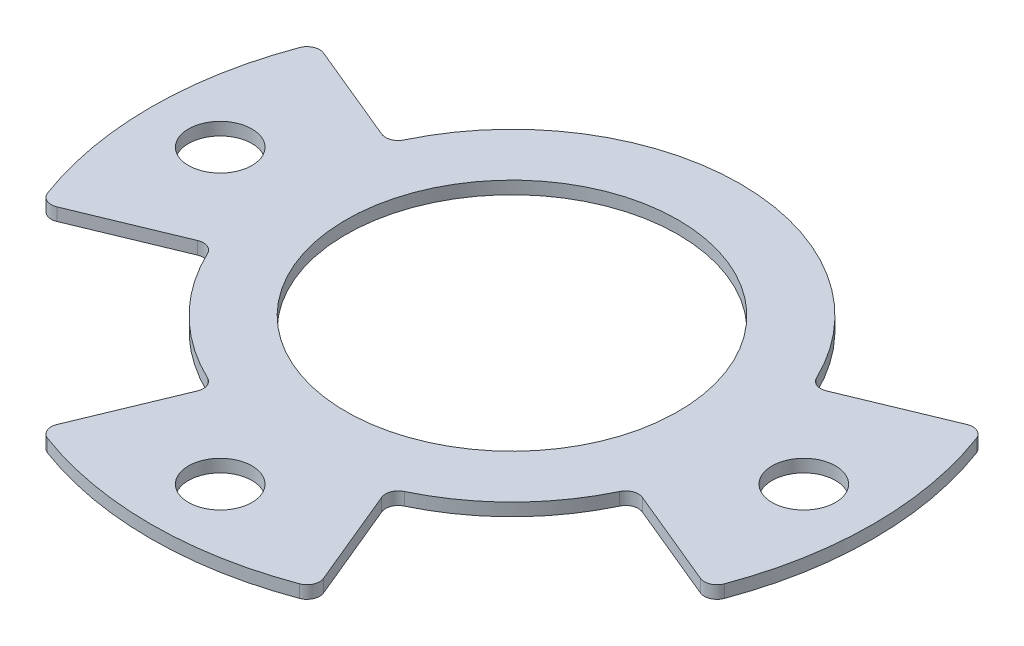
SolidWorks part; units mm, degrees
ref_plane "Front Plane" through (0, 0, 0) normal (0, 0, 1) x (1, 0, 0)
ref_plane "Top Plane" through (0, 0, 0) normal (0, 1, 0) x (1, 0, 0)
ref_plane "Right Plane" through (0, 0, 0) normal (1, 0, 0) x (0, 0, -1)
sketch "Sketch1" plane through (0, 0, 0) normal (0, 1, 0) x (1, 0, 0)
  circle A0 centre (0, 0) radius 72.3
  dimension "D1" = 144.6
extrude "Extrude1" add sketch "Sketch1" along normal blind 2.54
sketch "Sketch2" plane through (0, 0, 0) normal (0, -1, 0) x (1, 0, 0)
  line L0 (0, 0) -> (0, 46.2536) construction
  circle A0 centre (-58.42, 0) radius 6.35
  circle A1 centre (58.42, 0) radius 6.35
  circle A2 centre (0, 58.42) radius 6.35
  dimension "D1" = 12.7
  dimension "D2" = 12.7
  dimension "D3" = 116.84
  dimension "D4" = 58.42
extrude "Extrude2" cut sketch "Sketch2" against normal through all
sketch "Sketch3" plane through (0, 0, 0) normal (0, -1, 0) x (1, 0, 0)
  circle A0 centre (0, 0) radius 33.25
  dimension "D1" = 66.5
extrude "Extrude3" cut sketch "Sketch3" against normal through all
sketch "Sketch4" plane through (0, 0, 0) normal (0, -1, 0) x (1, 0, 0)
  line L0 (-42.2398, -17.4963) -> (-196.0271, -81.1971)
  line L1 (-196.0271, -81.1971) -> (196.0271, -81.1971)
  line L2 (196.0271, -81.1971) -> (42.2398, -17.4963)
  line L4 (0, 0) -> (0, 78.8399) construction
  line L5 (-42.2398, 17.4963) -> (-90.2628, 37.3881)
  line L6 (-90.2628, 37.3881) -> (-35.0925, 84.7207)
  line L7 (-35.0925, 84.7207) -> (-17.4963, 42.2398)
  line L8 (42.2398, 17.4963) -> (90.2628, 37.3881)
  line L9 (35.0925, 84.7207) -> (17.4963, 42.2398)
  line L10 (90.2628, 37.3881) -> (35.0925, 84.7207)
  arc A0 (-17.4963, 42.2398) -> (-42.2398, 17.4963) centre (0, 0) ccw
  arc A1 (17.4963, 42.2398) -> (42.2398, 17.4963) centre (0, 0) cw
  arc A2 (-42.2398, -17.4963) -> (42.2398, -17.4963) centre (0, 0) ccw
  dimension "D4" = 45.72
  dimension "D5" = 45.72
  dimension "D1" = 45
  dimension "D2" = 45
  dimension "D3" = 135
extrude "Extrude4" cut sketch "Sketch4" against normal blind 2.54
fillet "Fillet1" radius 2.54 12 edges at (-66.7965, 1.27, -27.668) (-42.2398, 1.27, -17.4963) (42.2398, 1.27, -17.4963) (66.7965, 1.27, -27.668) (66.7965, 1.27, 27.668) (42.2398, 1.27, 17.4963) (17.4963, 1.27, 42.2398) (27.668, 1.27, 66.7965) (-27.668, 1.27, 66.7965) (-17.4963, 1.27, 42.2398) (-42.2398, 1.27, 17.4963) (-66.7965, 1.27, 27.668)
